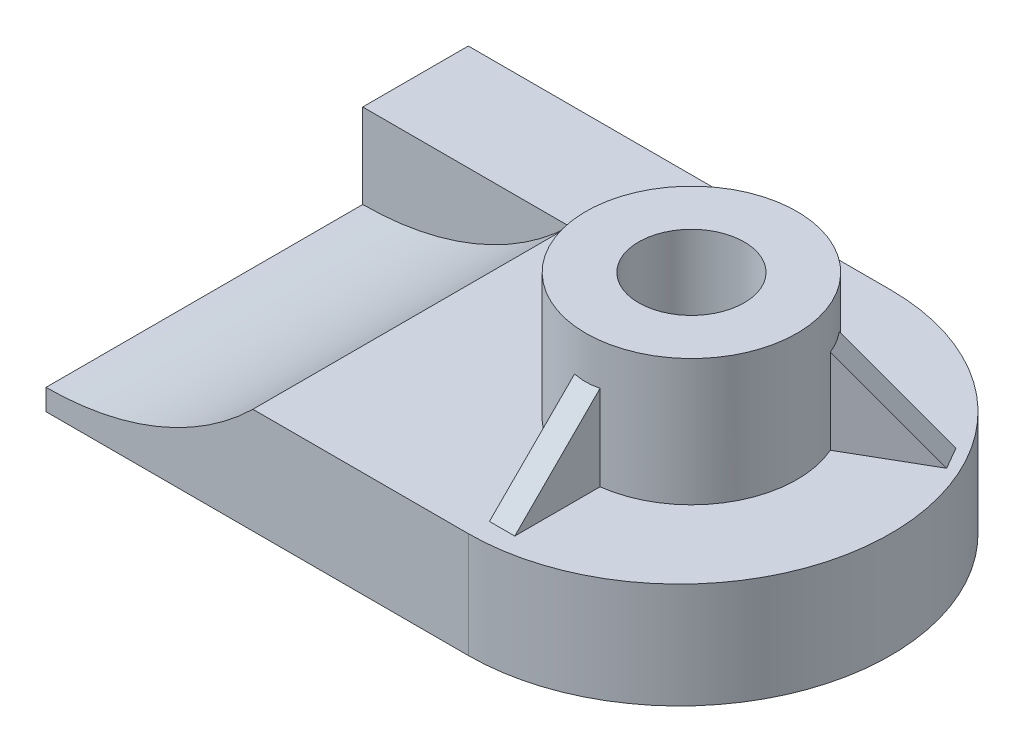
SolidWorks part; units mm, degrees
ref_plane "Front Plane" through (0, 0, 0) normal (0, 0, 1) x (1, 0, 0)
ref_plane "Top Plane" through (0, 0, 0) normal (0, 1, 0) x (1, 0, 0)
ref_plane "Right Plane" through (0, 0, 0) normal (1, 0, 0) x (0, 0, -1)
sketch "Sketch1" plane through (0, 0, 0) normal (0, 1, 0) x (1, 0, 0)
  line L5 (-50, 50) -> (50, 50)
  line L6 (-50, 50) -> (-50, -50)
  line L7 (-50, -50) -> (50, -50)
  line L9 (-50, 50) -> (50, -50) construction
  line L10 (-50, -50) -> (50, 50) construction
  arc A0 (50, 50) -> (50, -50) centre (50, 0) cw
  point P0 (0, 0)
  dimension "D3" = 50
  dimension "D1" = 100
  dimension "D2" = 100
extrude "Boss-Extrude1" add sketch "Sketch1" along normal blind 25
sketch "Sketch2" plane through (0, 0, 50) normal (0, 0, 1) x (1, 0, 0)
  line L1 (-50, 25) -> (-50, 0) construction
  line L2 (-50, 25) -> (50, 25) construction
  line L3 (-1.0102, 25) -> (-50, 25)
  line L4 (-50, 25) -> (-50, 5)
  arc A0 (-50, 5) -> (-1.0102, 25) centre (-50, 75) ccw
  dimension "D2" = 70
extrude "Cut-Extrude1" cut sketch "Sketch2" against normal blind 75
sketch "Sketch3" plane through (0, 25, 0) normal (0, 1, 0) x (1, 0, 0)
  line L1 (-1.0102, -50) -> (50, -50) construction
  circle A0 centre (52.839, 0) radius 25
  circle A1 centre (52.839, 0) radius 12.5
  arc A3 (50, -50) -> (50, 50) centre (50, 0) ccw construction
  point P5 (52.839, 0)
  point P7 (99.9809, 1.381)
  dimension "D1" = 50
  dimension "D2" = 25
  dimension "D3" = 50
extrude "Boss-Extrude2" add sketch "Sketch3" along normal blind 30
ref_plane "Plane1" through (53, 0, 0) normal (1, 0, 0) x (0, 0, -1)
sketch "Sketch5" plane through (53, 0, 0) normal (1, 0, 0) x (0, 0, -1)
  line L0 (-25, 45) -> (-45, 25)
  line L1 (-25, 55) -> (-25, 25) construction
  line L2 (50, 25) -> (-50, 25) construction
  dimension "D1" = 20
  dimension "D2" = 20
rib "Rib2" sketch "Sketch5" sketch "Sketch5" thickness 6 extrusion direction parallel to sketch draft on no parameters "D1"=6
pattern_circular "CirPattern1" count 3 over 360 about axis through (52.839, 0, 0) along (0, 1, 0) of "Rib2"
